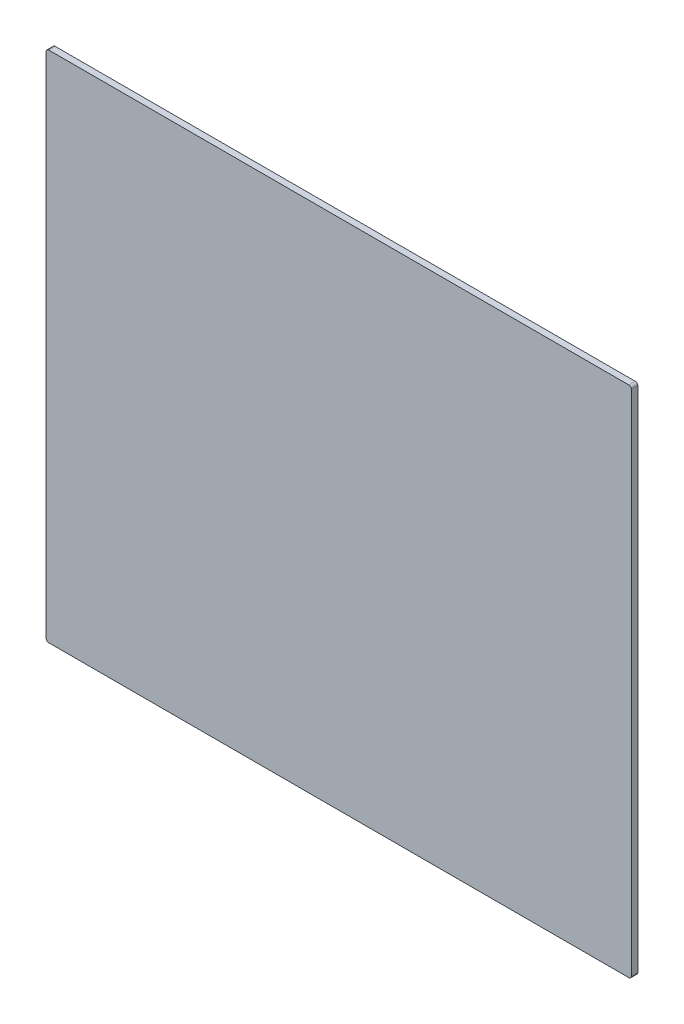
SolidWorks part; units mm, degrees
ref_plane "Plan de face" through (0, 0, 0) normal (0, 0, 1) x (1, 0, 0)
ref_plane "Plan de dessus" through (0, 0, 0) normal (0, 1, 0) x (1, 0, 0)
ref_plane "Plan de droite" through (0, 0, 0) normal (1, 0, 0) x (0, 0, -1)
sketch "Esquisse1" plane through (0, 0, 0) normal (0, 0, 1) x (1, 0, 0)
  line L1 (-452, -400) -> (452, -400)
  line L2 (-456, -396) -> (-456, 396)
  line L3 (-452, 400) -> (452, 400)
  line L4 (456, -396) -> (456, 396)
  line L5 (-456, -400) -> (456, 400) construction
  line L6 (-456, 400) -> (456, -400) construction
  arc A0 (-456, 396) -> (-452, 400) centre (-452, 396) cw
  arc A1 (456, 396) -> (452, 400) centre (452, 396) ccw
  arc A2 (452, -400) -> (456, -396) centre (452, -396) ccw
  arc A3 (-456, -396) -> (-452, -400) centre (-452, -396) ccw
  point P0 (0, 0)
  dimension "D3" = 4
  dimension "D4" = 4
  dimension "D5" = 4
  dimension "D6" = 4
  dimension "D1" = 912
  dimension "D2" = 800
extrude "Boss.-Extru.1" add sketch "Esquisse1" along normal blind 10
